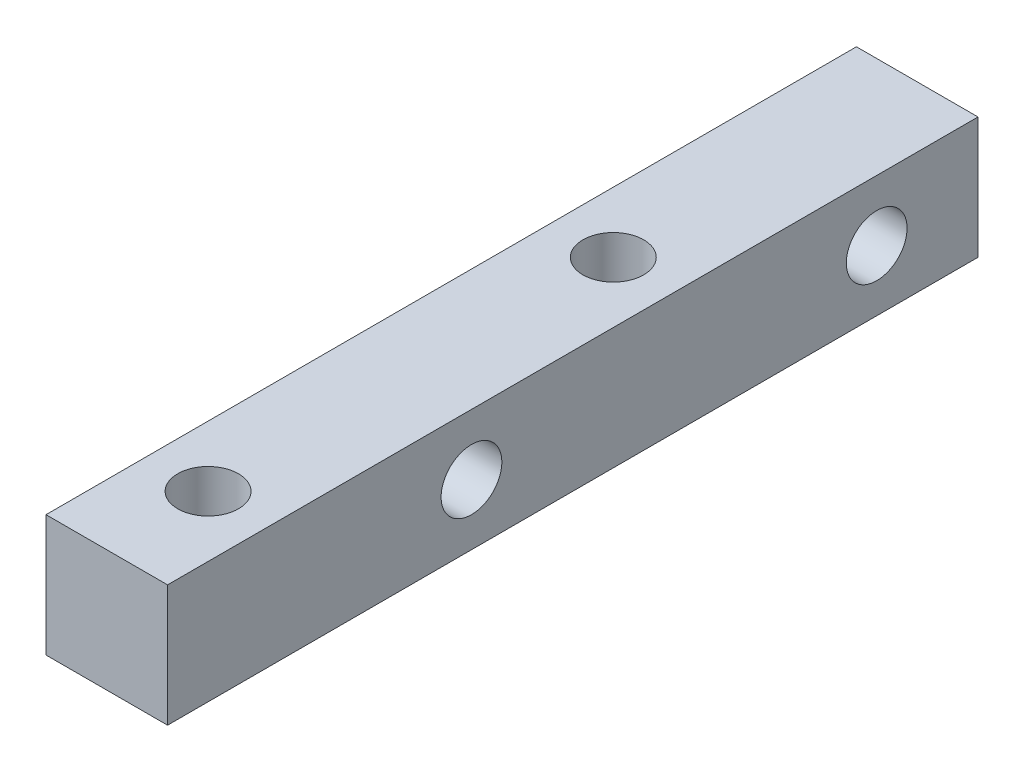
SolidWorks part; units mm, degrees
material "氧化铝"
ref_plane "前视基准面" through (0, 0, 0) normal (0, 0, 1) x (1, 0, 0)
ref_plane "上视基准面" through (0, 0, 0) normal (0, 1, 0) x (1, 0, 0)
ref_plane "右视基准面" through (0, 0, 0) normal (1, 0, 0) x (0, 0, -1)
other "Configuration Table"
sketch "草图1" plane through (0, 0, 0) normal (0, 0, 1) x (1, 0, 0)
  line L1 (-3, -3) -> (3, -3)
  line L2 (-3, -3) -> (-3, 3)
  line L3 (-3, 3) -> (3, 3)
  line L4 (3, -3) -> (3, 3)
  line L5 (-3, -3) -> (3, 3) construction
  line L6 (-3, 3) -> (3, -3) construction
  point P0 (0, 0)
  dimension "D1" = 6
extrude "凸台-拉伸1" add sketch "草图1" against normal blind 40
sketch "草图2" plane through (0, 3, 0) normal (0, 1, 0) x (1, 0, 0)
  line L0 (0, 0) -> (0, 40) construction
  line L1 (3, 0) -> (-3, 0) construction
  line L2 (3, 40) -> (-3, 40) construction
  circle A0 centre (0, 5) radius 1.5
  dimension "D1" = 3
  dimension "D2" = 5
extrude "切除-拉伸1" cut sketch "草图2" against normal through all
sketch "草图3" plane through (3, 0, 0) normal (1, 0, 0) x (0, 0, -1)
  line L0 (40, 0) -> (0, 0) construction
  line L1 (40, -3) -> (40, 3) construction
  circle A0 centre (35, 0) radius 1.5
  dimension "D2" = 3
  dimension "D1" = 5
extrude "切除-拉伸2" cut sketch "草图3" against normal through all
pattern_linear "阵列(线性)1" count 2 spacing 20 along (0, 0, -1) of "切除-拉伸1"
pattern_linear "阵列(线性)2" count 2 spacing 20 along (0, 0, 1) of "切除-拉伸2"
sketch "草图4" plane through (3, 0, 0) normal (1, 0, 0) x (0, 0, -1)
  line L0 (20, 3) -> (20, -3) construction
  line L1 (40, 3) -> (0, 3) construction
  line L2 (40, -3) -> (0, -3) construction
  circle A0 centre (20, 0) radius 2
  dimension "D1" = 4
extrude "切除-拉伸3" [suppressed] cut sketch "草图4" against normal through all
equation "\"D\"= 6'宽"
equation "\"L\"= 40'长"
equation "\"H1\"= 5'孔边距"
equation "\"H2\"= 20'孔距"
equation "\"D1@草图1\"=\"D\""
equation "\"D1@凸台-拉伸1\"=\"L\""
equation "\"D2@草图2\"=\"H1\""
equation "\"D1@草图3\"=\"H1\""
equation "\"D3@阵列(线性)1\"=\"H2\""
equation "\"D3@阵列(线性)2\"=\"H2\""
